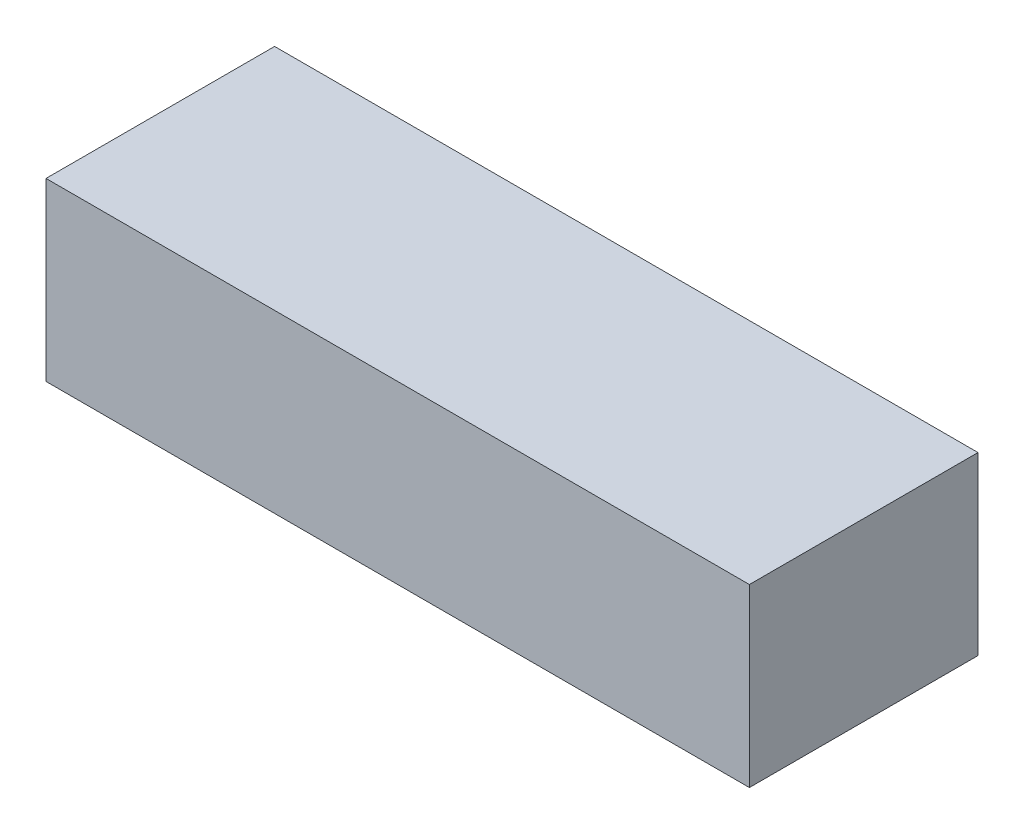
SolidWorks part; units mm, degrees
ref_plane "Front Plane" through (0, 0, 0) normal (0, 0, 1) x (1, 0, 0)
ref_plane "Top Plane" through (0, 0, 0) normal (0, 1, 0) x (1, 0, 0)
ref_plane "Right Plane" through (0, 0, 0) normal (1, 0, 0) x (0, 0, -1)
sketch "Sketch1" plane through (0, 0, 0) normal (0, 1, 0) x (1, 0, 0)
  line L1 (0, 0) -> (40, 0)
  line L2 (0, 0) -> (0, 13)
  line L3 (0, 13) -> (40, 13)
  line L4 (40, 0) -> (40, 13)
extrude "Boss-Extrude1" add sketch "Sketch1" against normal blind 10
